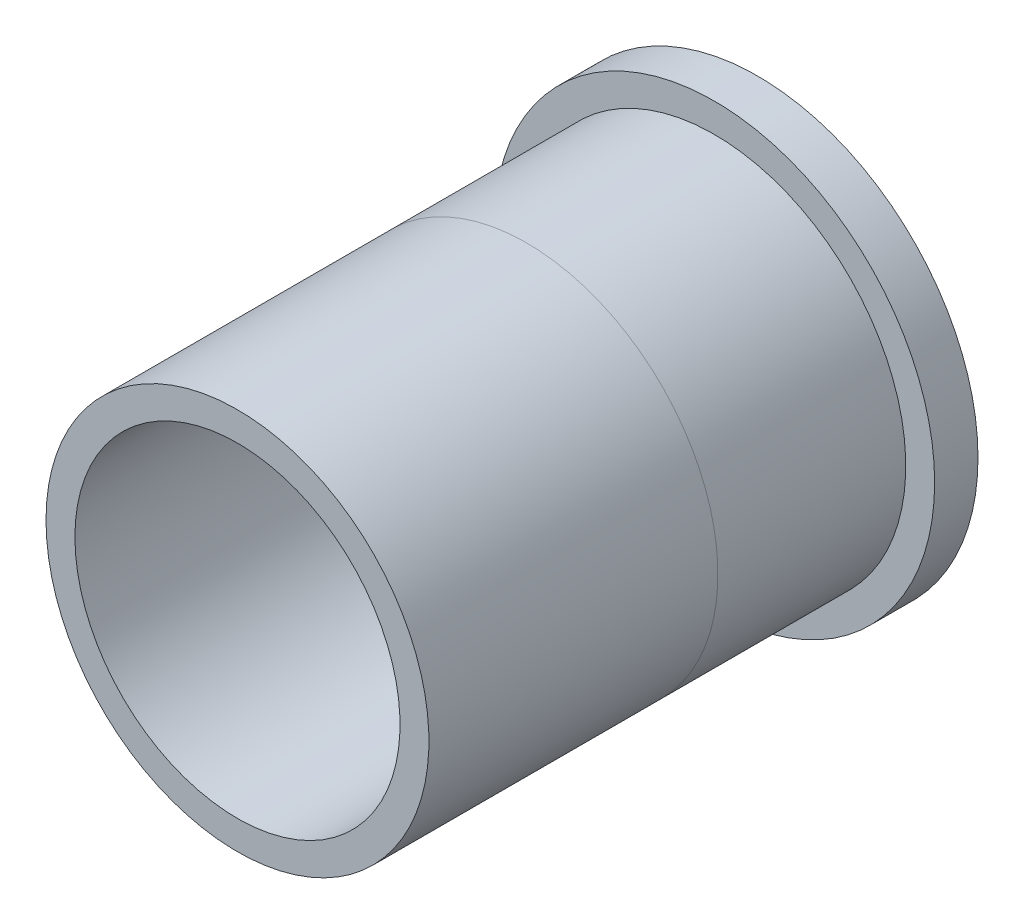
SolidWorks part; units mm, degrees
ref_plane "Alzado" through (0, 0, 0) normal (0, 0, 1) x (1, 0, 0)
ref_plane "Planta" through (0, 0, 0) normal (0, 1, 0) x (1, 0, 0)
ref_plane "Vista lateral" through (0, 0, 0) normal (1, 0, 0) x (0, 0, -1)
sketch "Croquis1" plane through (0, 0, 0) normal (0, 1, 0) x (1, 0, 0)
  line L0 (0, 41.7455) -> (0, -38.8945) construction
  line L1 (11.25, -6.5805) -> (11.25, 20.1436)
  line L2 (11.25, -6.5805) -> (13.25, -6.5805)
  line L3 (13.25, -6.5805) -> (13.25, 26.4195)
  line L4 (13.25, 26.4195) -> (15.25, 26.4195)
  line L5 (15.25, 26.4195) -> (15.25, 29.4195)
  line L6 (15.25, 29.4195) -> (12.25, 29.4195)
  line L7 (12.25, 29.4195) -> (12.25, 26.4436)
  line L8 (12.25, 26.4436) -> (8.75, 26.4436)
  line L9 (8.75, 26.4436) -> (8.75, 26.1436)
  line L10 (8.75, 26.1436) -> (4, 26.1436)
  line L11 (4, 26.1436) -> (4, 20.1436)
  line L12 (4, 20.1436) -> (11.25, 20.1436)
  dimension "D1" = 11.25
  dimension "D2" = 3
  dimension "D3" = 2
  dimension "D4" = 3
  dimension "D5" = 2
  dimension "D6" = 3.5
  dimension "D7" = 4
  dimension "D8" = 0.3
  dimension "D9" = 6
  dimension "D10" = 36
revolve "Revolución1" add sketch "Croquis1" angle 360 about L0
ref_plane "Plano1" through (0, 0, -13.4195) normal (0, 0, -1) x (-1, 0, 0)
split "Partir1" trim tools "Plano1" bodies to split 101 resulting bodies 102 103
